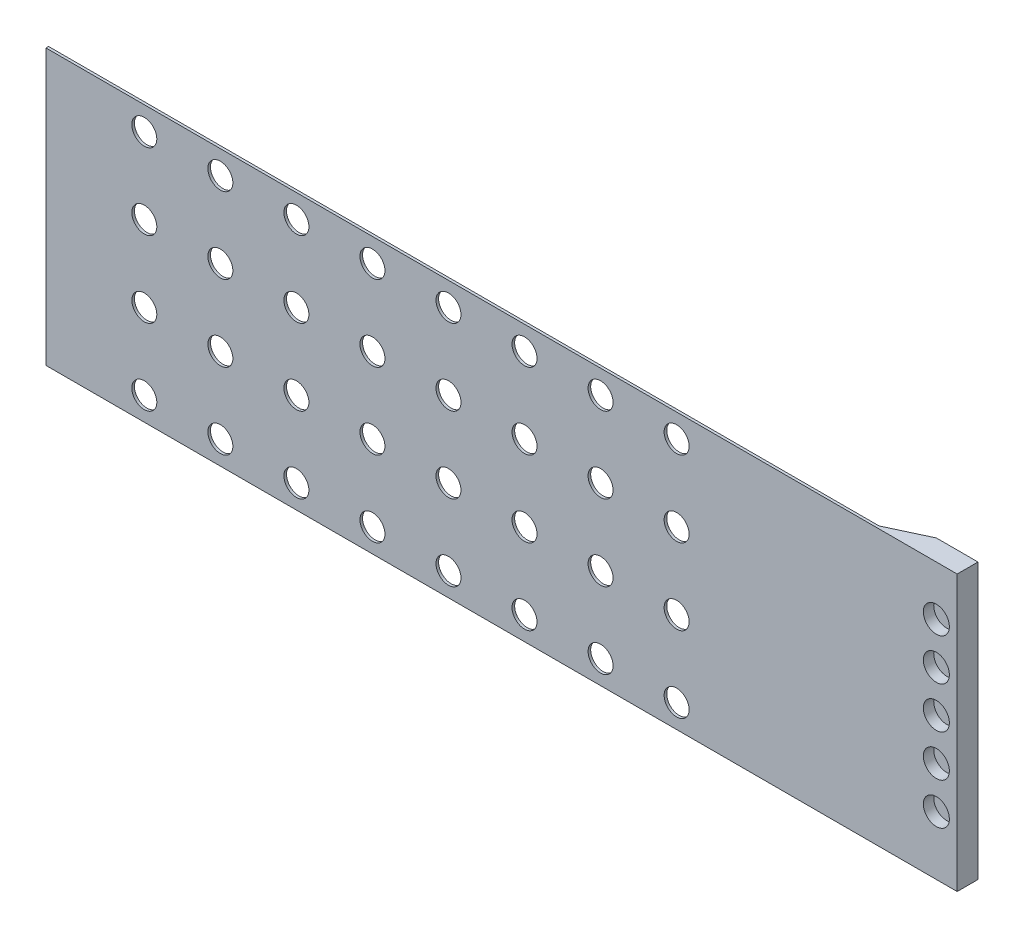
SolidWorks part; units mm, degrees
ref_plane "Front Plane" through (0, 0, 0) normal (0, 0, 1) x (1, 0, 0)
ref_plane "Top Plane" through (0, 0, 0) normal (0, 1, 0) x (1, 0, 0)
ref_plane "Right Plane" through (0, 0, 0) normal (1, 0, 0) x (0, 0, -1)
sketch "Sketch1" plane through (0, 0, 0) normal (0, 0, 1) x (1, 0, 0)
  line L1 (-64, -25.8075) -> (64, -25.8075) construction
  line L2 (-64, -25.8075) -> (-64, 25.8075) construction
  line L3 (-64, 25.8075) -> (64, 25.8075) construction
  line L4 (64, -25.8075) -> (64, 25.8075) construction
  line L5 (-64, -25.8075) -> (64, 25.8075) construction
  line L6 (-64, 25.8075) -> (64, -25.8075) construction
  line L7 (-125, -50) -> (125, -50)
  line L8 (-125, -50) -> (-125, 50)
  line L9 (-125, 50) -> (125, 50)
  line L10 (125, -50) -> (125, 50)
  line L11 (-125, -50) -> (125, 50) construction
  line L12 (-125, 50) -> (125, -50) construction
  point P0 (0, 0)
  point P6 (0, 0)
  point P7 (0, 0)
  dimension "D1" = 128
  dimension "D2" = 51.615
  dimension "D3" = 250
  dimension "D4" = 100
extrude "Boss-Extrude1" add sketch "Sketch1" along normal mid plane 0.5
sketch "Sketch2" plane through (0, 0, 0.25) normal (0, 0, 1) x (1, 0, 0)
  line L5 (-64, -32) -> (64, -32) construction
  line L6 (-64, -32) -> (-64, 32) construction
  line L7 (-64, 32) -> (64, 32) construction
  line L8 (64, -32) -> (64, 32) construction
  line L9 (-64, -32) -> (64, 32) construction
  line L10 (-64, 32) -> (64, -32) construction
  circle A0 centre (-51.1175, -22.8) radius 2.4
  circle A1 centre (-36.5125, -22.8) radius 2.4
  circle A2 centre (-21.9075, -22.8) radius 2.4
  circle A3 centre (-7.3025, -22.8) radius 2.4
  circle A4 centre (7.3025, -22.8) radius 2.4
  circle A5 centre (21.9075, -22.8) radius 2.4
  circle A6 centre (36.5125, -22.8) radius 2.4
  circle A7 centre (51.1175, -22.8) radius 2.4
  circle A8 centre (-36.5125, -8.195) radius 2.4
  circle A9 centre (-21.9075, -8.195) radius 2.4
  circle A10 centre (-7.3025, -8.195) radius 2.4
  circle A11 centre (7.3025, -8.195) radius 2.4
  circle A12 centre (21.9075, -8.195) radius 2.4
  circle A13 centre (36.5125, -8.195) radius 2.4
  circle A14 centre (51.1175, -8.195) radius 2.4
  circle A15 centre (-36.5125, 6.41) radius 2.4
  circle A16 centre (-21.9075, 6.41) radius 2.4
  circle A17 centre (-7.3025, 6.41) radius 2.4
  circle A18 centre (7.3025, 6.41) radius 2.4
  circle A19 centre (21.9075, 6.41) radius 2.4
  circle A20 centre (36.5125, 6.41) radius 2.4
  circle A21 centre (51.1175, 6.41) radius 2.4
  circle A22 centre (-36.5125, 21.015) radius 2.4
  circle A23 centre (-21.9075, 21.015) radius 2.4
  circle A24 centre (-7.3025, 21.015) radius 2.4
  circle A25 centre (7.3025, 21.015) radius 2.4
  circle A26 centre (21.9075, 21.015) radius 2.4
  circle A27 centre (36.5125, 21.015) radius 2.4
  circle A28 centre (51.1175, 21.015) radius 2.4
  circle A29 centre (-51.1175, -8.195) radius 2.4
  circle A30 centre (-51.1175, 6.41) radius 2.4
  circle A31 centre (-51.1175, 21.015) radius 2.4
  point P72 (0, 0)
  dimension "D1" = 9.2
  dimension "D3" = 4.8
  dimension "D6" = 14.605
  dimension "D2" = 12.8825
  dimension "D7" = 14.605
  dimension "D8" = 12.8825
  dimension "D9" = 10.985
  dimension "D4" = 8
  dimension "D5" = 4
extrude "Cut-Extrude1" cut sketch "Sketch2" against normal through all
sketch "Sketch3" plane through (0, 0, 0.25) normal (0, 0, 1) x (1, 0, 0)
  line L0 (-70, 25.515) -> (-70, -27.3)
  line L1 (0, 0) -> (0, 71.3385) construction
  line L2 (64, -32) -> (64, 32) construction
  line L5 (-64, -32) -> (-64, 32) construction
  line L6 (0, 0) -> (50000, 0) construction
  line L7 (-70, 25.515) -> (105, 25.515)
  line L15 (-70, -27.3) -> (105, -27.3)
  line L16 (105, 25.515) -> (105, -27.3)
  line L17 (-119.034, 30.9489) -> (105, -27.3) construction
  line L18 (-120.0889, -29.1816) -> (105, 25.515) construction
  circle A1 centre (-51.1175, -22.8) radius 2.4 construction
  circle A3 centre (-51.1175, 21.015) radius 2.4 construction
  point P4 (-51.1175, -25.2)
  point P5 (-51.1175, 23.415)
  point P15 (0, 0)
  point P18 (0, 0)
  dimension "D1" = 4.5
  dimension "D3" = 41
  dimension "D2" = 52.815
  dimension "D4" = 6
  dimension "D5" = 4.5
  dimension "D6" = 175
extrude "Cut-Extrude-Thin1" cut sketch "Sketch3" against normal through all thin
sketch "Sketch6" plane through (0, 0, -0.25) normal (0, 0, -1) x (-1, 0, 0)
  line L0 (70, -27.3) -> (-105, -27.3) construction
  line L1 (-105, 25.515) -> (-97, 25.515)
  line L2 (-105, 25.515) -> (-105, -27.3)
  line L3 (-105, -27.3) -> (-97, -27.3)
  line L4 (-97, 25.515) -> (-97, -27.3)
  dimension "D1" = 8
extrude "Boss-Extrude3" add sketch "Sketch6" along normal blind 3.5
sketch "Sketch5" plane through (0, 0, 0.25) normal (0, 0, 1) x (1, 0, 0)
  line L0 (0, 72.6953) -> (0, -72.6953) construction
  line L1 (101, 35.9159) -> (101, -38.5788) construction
  line L2 (105, -27.3) -> (105, 25.515) construction
  line L3 (0, 0) -> (12.6967, 0) construction
  circle A16 centre (101, -16) radius 2.5
  circle A17 centre (101, -8) radius 2.5
  circle A18 centre (101, 0) radius 2.5
  circle A19 centre (101, 8) radius 2.5
  circle A20 centre (101, 16) radius 2.5
  point P7 (0, 0)
  dimension "D1" = 4
  dimension "D2" = 5
extrude "Cut-Extrude2" cut sketch "Sketch5" against normal blind 2 and the other way through all
sketch "Sketch8" plane through (0, 25.515, 0) normal (0, 1, 0) x (1, 0, 0)
  line L0 (89.5, 0.25) -> (97, 3.75)
  line L1 (97, 0.25) -> (-70, 0.25) construction
  line L2 (97, 3.75) -> (97, 0.25)
  line L3 (97, 0.25) -> (89.5, 0.25)
  dimension "D1" = 7.5
  dimension "D2" = 3.5
extrude "Boss-Extrude4" add sketch "Sketch8" against normal through all
